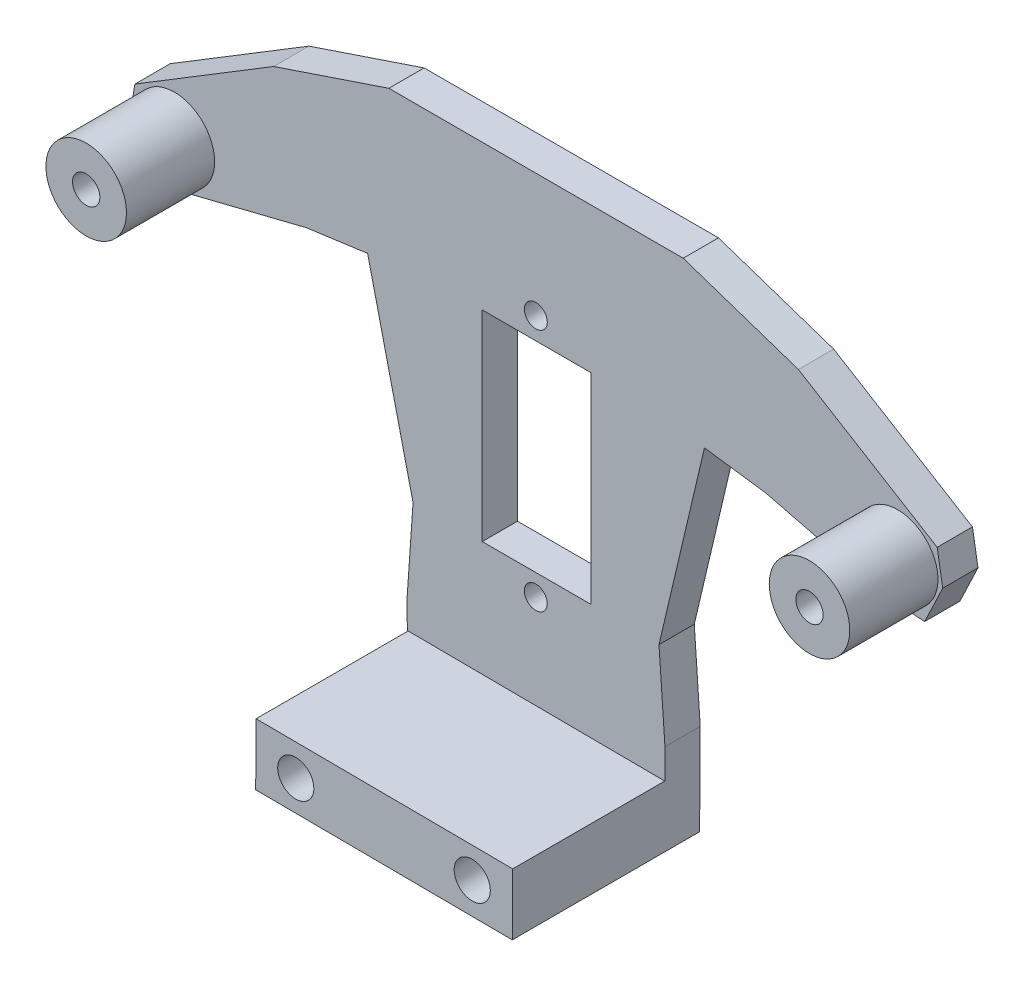
SolidWorks part; units mm, degrees
other "Markup1"
sketch "Sketch21" plane through (-46.1137, 29.5171, 21.24) normal (-0.2546, 0.0917, 0.9627) x (0.9504, 0.2077, 0.2316)
material "PLA"
ref_plane "Front Plane" through (0, 0, 0) normal (0, 0, 1) x (1, 0, 0)
ref_plane "Top Plane" through (0, 0, 0) normal (0, 1, 0) x (1, 0, 0)
ref_plane "Right Plane" through (0, 0, 0) normal (1, 0, 0) x (0, 0, -1)
sketch "Sketch1" plane through (0, 0, 0) normal (0, 0, 1) x (1, 0, 0)
  line L0 (-16.6877, 29.5171) -> (16.6877, 29.5171)
  line L1 (16.6877, 29.5171) -> (29.7517, 25.1271)
  line L2 (29.7517, 25.1271) -> (45.4857, 15.5331)
  line L3 (45.4857, 15.5331) -> (46.1157, 11.8291)
  line L4 (46.1157, 11.8291) -> (44.0657, 7.5251)
  line L5 (44.0657, 7.5251) -> (39.5277, 7.7851)
  line L6 (39.5277, 7.7851) -> (26.0577, 11.1431)
  line L7 (26.0577, 11.1431) -> (19.0957, 12.0991)
  line L8 (19.0957, 12.0991) -> (13.9437, -9.7989)
  line L9 (13.9437, -9.7989) -> (14.6177, -19.4889)
  line L10 (14.6177, -19.4889) -> (14.5497, -29.8729)
  line L11 (14.5497, -29.8729) -> (-14.5497, -29.8729)
  line L12 (-14.5497, -29.8729) -> (-14.6197, -19.4889)
  line L13 (-14.6197, -19.4889) -> (-13.9457, -9.7989)
  line L14 (-13.9457, -9.7989) -> (-19.0977, 12.0991)
  line L15 (-19.0977, 12.0991) -> (-26.0597, 11.1431)
  line L16 (-26.0597, 11.1431) -> (-39.5297, 7.7851)
  line L17 (-39.5297, 7.7851) -> (-44.0677, 7.5251)
  line L18 (-44.0677, 7.5251) -> (-46.1137, 11.8291)
  line L19 (-46.1137, 11.8291) -> (-45.4857, 15.5331)
  line L20 (-45.4857, 15.5331) -> (-29.7517, 25.1271)
  line L21 (-29.7517, 25.1271) -> (-16.6877, 29.5171)
  point P22 (0, -29.8729)
  point P24 (0, 29.5171)
extrude "Boss-Extrude1" add sketch "Sketch1" along normal blind 4
sketch "Sketch2" plane through (0, 0, 4) normal (0, 0, 1) x (1, 0, 0)
  line L1 (-6.1, 13.0471) -> (6.25, 13.0471)
  line L2 (-6.1, 13.0471) -> (-6.1, -9.7029)
  line L3 (-6.1, -9.7029) -> (6.25, -9.7029)
  line L4 (6.25, 13.0471) -> (6.25, -9.7029)
  line L6 (-6.1, 13.0471) -> (-6.1, -9.5529)
  line L7 (-6.1, -9.5529) -> (6.1, -9.5529)
  line L8 (6.1, 13.0471) -> (6.1, -9.5529)
  line L9 (-6.1, 13.0471) -> (6.1, 13.0471)
  dimension "D1" = 12.35
  dimension "D2" = 22.75
sketch "Sketch4" plane through (0, 0, 4) normal (0, 0, 1) x (1, 0, 0)
  line L2 (0, -2.2) -> (0, 2.2) construction
  circle A0 centre (10.005, -26.2729) radius 2.05
  circle A2 centre (-10.005, -26.2729) radius 2.05
  point P2 (12.055, -26.2729)
  dimension "D1" = 4.1
  dimension "D4" = 4.1
  dimension "D2" = 20.01
sketch "Sketch6" plane through (0, 0, 4) normal (0, 0, 1) x (1, 0, 0)
  line L4 (0, -2.2) -> (0, 2.2) construction
  circle A0 centre (-41.0088, 12.4151) radius 4.5665
  circle A1 centre (41.0088, 12.4151) radius 4.5665
extrude "Cut-Extrude10" cut sketch "Sketch2" against normal through all contours L4 L1 L2 L3 | L8 L1 L2 L7
extrude "Boss-Extrude3" add sketch "Sketch6" along normal blind 10
extrude "Cut-Extrude11" cut sketch "Sketch4" against normal blind 9.65
sketch "Sketch15" plane through (0, 0, 4) normal (0, 0, 1) x (1, 0, 0)
  line L0 (-6.1, -9.7029) -> (6.25, -9.7029) construction
  line L2 (-6.1, 13.0471) -> (6.25, 13.0471) construction
  circle A0 centre (-0.0263, -12.1329) radius 1.3
  circle A1 centre (-0.0243, 15.5271) radius 1.3
  dimension "D1" = 2.6
  dimension "D2" = 2.43
  dimension "D3" = 13.97
  dimension "D4" = 13.9193
  dimension "D5" = 2.6
  dimension "D6" = 2.48
  dimension "D7" = 19.12
  dimension "D8" = 19.0733
extrude "Cut-Extrude13" cut sketch "Sketch15" against normal blind 9.65
sketch "Sketch17" plane through (0, 0, 14) normal (0, 0, 1) x (1, 0, 0)
  line L0 (0, -2.2) -> (0, 2.2) construction
  circle A0 centre (41.0088, 12.4151) radius 1.55
  circle A1 centre (-41.0088, 12.4151) radius 1.55
  dimension "D1" = 3.1
sketch "Sketch20" plane through (14.7446, -0.0966, 0) normal (1, -0.0065, 0) x (0, 0, -1)
  line L0 (-4, -29.777) -> (-4, -19.3927) construction
  line L1 (-21.24, -22.777) -> (-4, -22.777)
  line L2 (-21.24, -22.777) -> (-21.24, -29.777)
  line L3 (-21.24, -29.777) -> (-4, -29.777)
  line L4 (-4, -22.777) -> (-4, -29.777)
  line L5 (-4, -29.777) -> (0, -29.777) construction
  dimension "D1" = 17.24
  dimension "D2" = 7
extrude "Boss-Extrude4" add sketch "Sketch20" against normal blind 29.1
sketch "Sketch14" plane through (0, 0, 4) normal (0, 0, 1) x (1, 0, 0)
  circle A0 centre (-10.005, -26.2729) radius 2.05
  circle A1 centre (10.005, -26.2729) radius 2.05
  dimension "D1" = 4.1
  dimension "D2" = 4.1
  dimension "D3" = 20.01
extrude "Cut-Extrude16" cut sketch "Sketch14" along normal through all
extrude "Cut-Extrude17" cut sketch "Sketch17" against normal through all
